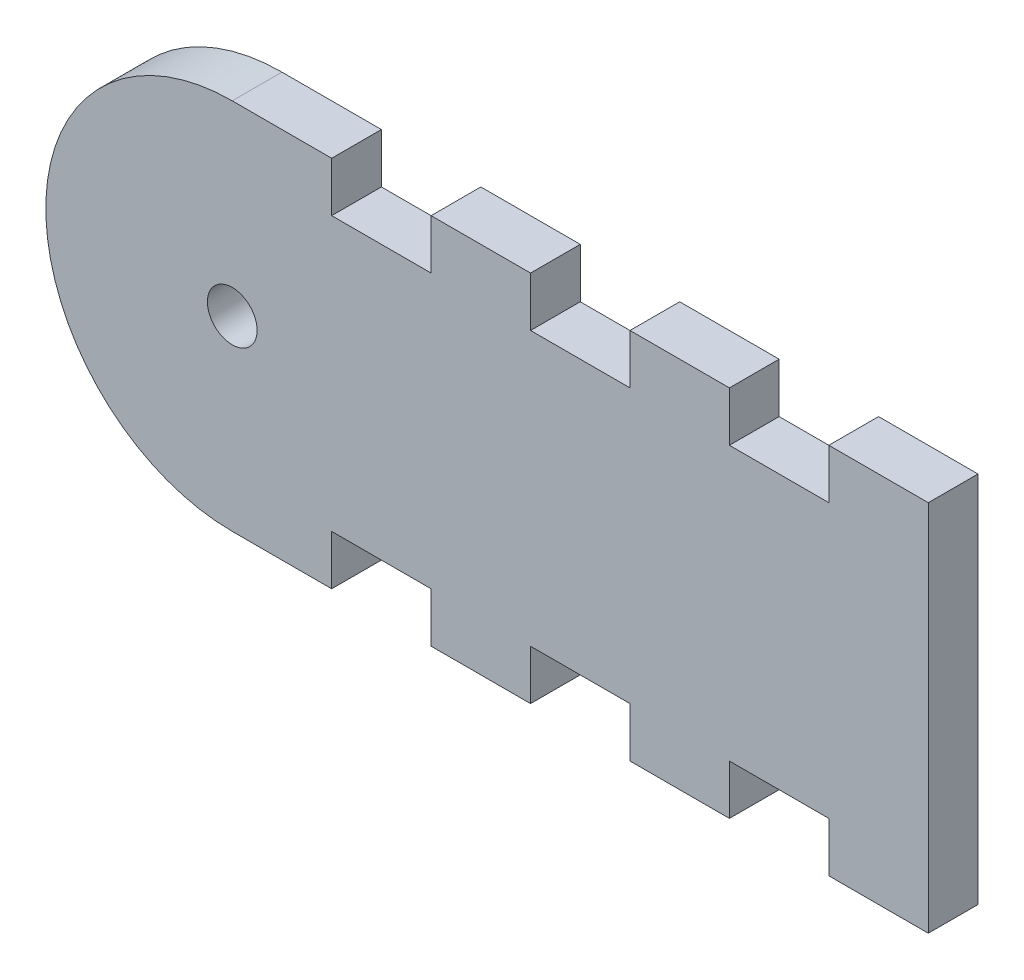
SolidWorks part; units mm, degrees
ref_plane "Front Plane" through (0, 0, 0) normal (0, 0, 1) x (1, 0, 0)
ref_plane "Top Plane" through (0, 0, 0) normal (0, 1, 0) x (1, 0, 0)
ref_plane "Right Plane" through (0, 0, 0) normal (1, 0, 0) x (0, 0, -1)
sketch "Sketch1" plane through (0, 0, 0) normal (0, 0, 1) x (1, 0, 0)
  line L1 (-44.45, -23.8125) -> (44.45, -23.8125)
  line L2 (-44.45, -23.8125) -> (-44.45, 23.8125) construction
  line L3 (-44.45, 23.8125) -> (44.45, 23.8125)
  line L4 (44.45, -23.8125) -> (44.45, 23.8125)
  line L5 (-44.45, -23.8125) -> (44.45, 23.8125) construction
  line L6 (-44.45, 23.8125) -> (44.45, -23.8125) construction
  arc A0 (-44.45, 23.8125) -> (-44.45, -23.8125) centre (-44.45, 0) ccw
  point P0 (0, 0)
  dimension "D1" = 47.625
  dimension "D2" = 88.9
extrude "Mass" add sketch "Sketch1" along normal blind 6.35
sketch "Sketch3" plane through (0, 0, 0) normal (0, 0, -1) x (-1, 0, 0)
  line L1 (-44.45, 23.8125) -> (44.45, 23.8125) construction
  line L2 (44.45, -23.8125) -> (-44.45, -23.8125) construction
  line L3 (-44.45, 23.8125) -> (-31.75, 23.8125) construction
  line L5 (-19.05, 17.4625) -> (-31.75, 17.4625)
  line L6 (-19.05, 17.4625) -> (-19.05, 30.1625)
  line L7 (-19.05, 30.1625) -> (-31.75, 30.1625)
  line L8 (-31.75, 17.4625) -> (-31.75, 30.1625)
  line L9 (-19.05, 17.4625) -> (-31.75, 30.1625) construction
  line L10 (-19.05, 30.1625) -> (-31.75, 17.4625) construction
  line L11 (-19.05, -30.1625) -> (-31.75, -30.1625)
  line L12 (-19.05, -30.1625) -> (-19.05, -17.4625)
  line L13 (-19.05, -17.4625) -> (-31.75, -17.4625)
  line L14 (-31.75, -30.1625) -> (-31.75, -17.4625)
  line L15 (-19.05, -30.1625) -> (-31.75, -17.4625) construction
  line L16 (-19.05, -17.4625) -> (-31.75, -30.1625) construction
  point P3 (-25.4, 23.8125)
  point P4 (-25.4, -23.8125)
  dimension "D1" = 12.7
  dimension "D2" = 12.7
  dimension "D3" = 12.7
sketch "Sketch4" plane through (0, 0, 0) normal (0, 0, -1) x (-1, 0, 0)
  circle A0 centre (44.45, 0) radius 3.175
  arc A1 (44.45, -23.8125) -> (44.45, 23.8125) centre (44.45, 0) ccw construction
  dimension "D1" = 6.35
extrude "Cut-Extrude1" cut sketch "Sketch4" against normal through all
extrude "Cut-Extrude2" cut sketch "Sketch3" against normal through all
pattern_linear "LPattern1" count 3 spacing 25.4 along (-1, 0, 0) of "Cut-Extrude2"
